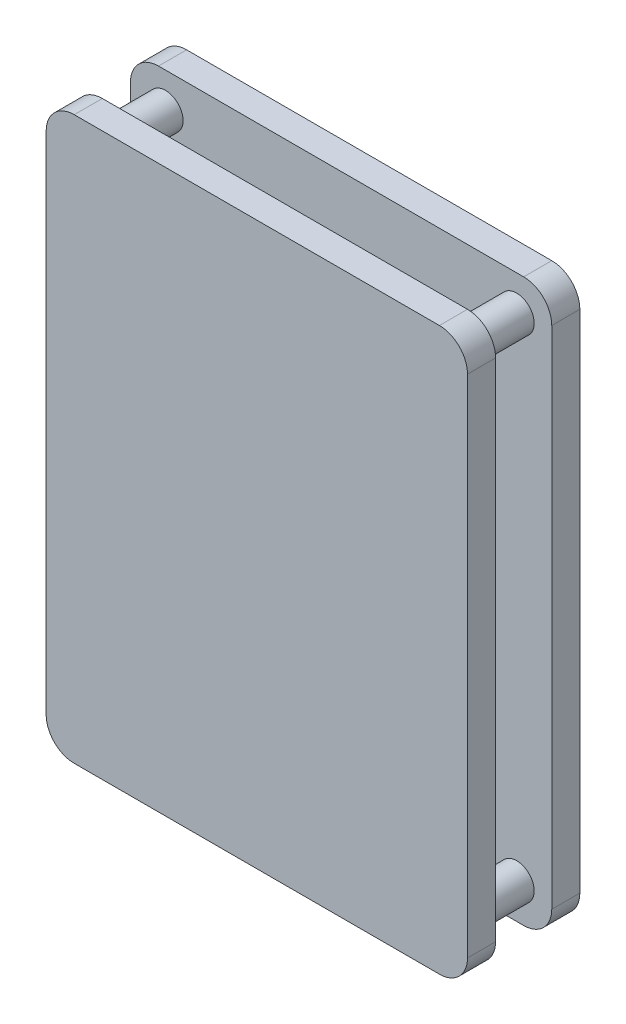
SolidWorks part; units mm, degrees
ref_plane "Front Plane" through (0, 0, 0) normal (0, 0, 1) x (1, 0, 0)
ref_plane "Top Plane" through (0, 0, 0) normal (0, 1, 0) x (1, 0, 0)
ref_plane "Right Plane" through (0, 0, 0) normal (1, 0, 0) x (0, 0, -1)
sketch "Sketch1" plane through (0, 0, 0) normal (0, 0, 1) x (1, 0, 0)
  line L0 (-68.5859, -300) -> (-68.5859, 60) construction
  line L1 (-83.5859, -160) -> (-53.5859, -160)
  line L2 (-83.5859, -160) -> (-83.5859, -200)
  line L3 (-83.5859, -200) -> (-53.5859, -200)
  line L4 (-53.5859, -160) -> (-53.5859, -200)
  dimension "D1" = 40
  dimension "D2" = 30
  dimension "D3" = 15
  dimension "D4" = 100
extrude "Boss-Extrude1" add sketch "Sketch1" along normal blind 2
fillet "Fillet1" radius 2 4 edges at (-53.5859, -160, 1) (-83.5859, -160, 1) (-53.5859, -200, 1) (-83.5859, -200, 1)
sketch "Sketch2" plane through (0, 0, 2) normal (0, 0, 1) x (1, 0, 0)
  line L0 (-83.5859, -180) -> (-53.5859, -180) construction
  line L1 (-83.5859, -162) -> (-83.5859, -198) construction
  line L2 (-53.5859, -198) -> (-53.5859, -162) construction
  line L3 (-68.5859, -160) -> (-68.5859, -200) construction
  line L4 (-55.5859, -160) -> (-81.5859, -160) construction
  line L5 (-81.5859, -200) -> (-55.5859, -200) construction
  circle A0 centre (-81.0859, -197.5) radius 1.25
  circle A1 centre (-56.0859, -197.5) radius 1.25
  circle A2 centre (-56.0859, -162.5) radius 1.25
  circle A3 centre (-81.0859, -162.5) radius 1.25
extrude "Boss-Extrude2" add sketch "Sketch2" along normal blind 4
sketch "Sketch3" plane through (0, 0, 6) normal (0, 0, 1) x (1, 0, 0)
  line L4 (-53.5859, -198) -> (-53.5859, -162)
  line L5 (-55.5859, -160) -> (-81.5859, -160)
  line L6 (-83.5859, -162) -> (-83.5859, -198)
  line L7 (-81.5859, -200) -> (-55.5859, -200)
  line L8 (-53.5859, -198) -> (-53.5859, -162)
  line L9 (-55.5859, -160) -> (-81.5859, -160)
  line L10 (-83.5859, -162) -> (-83.5859, -198)
  line L11 (-81.5859, -200) -> (-55.5859, -200)
  arc A4 (-53.5859, -162) -> (-55.5859, -160) centre (-55.5859, -162) ccw
  arc A5 (-81.5859, -160) -> (-83.5859, -162) centre (-81.5859, -162) ccw
  arc A6 (-83.5859, -198) -> (-81.5859, -200) centre (-81.5859, -198) ccw
  arc A7 (-55.5859, -200) -> (-53.5859, -198) centre (-55.5859, -198) ccw
  arc A8 (-53.5859, -162) -> (-55.5859, -160) centre (-55.5859, -162) ccw
  arc A9 (-81.5859, -160) -> (-83.5859, -162) centre (-81.5859, -162) ccw
  arc A10 (-83.5859, -198) -> (-81.5859, -200) centre (-81.5859, -198) ccw
  arc A11 (-55.5859, -200) -> (-53.5859, -198) centre (-55.5859, -198) ccw
  dimension "D1" = 0
extrude "Boss-Extrude3" add sketch "Sketch3" along normal blind 2
